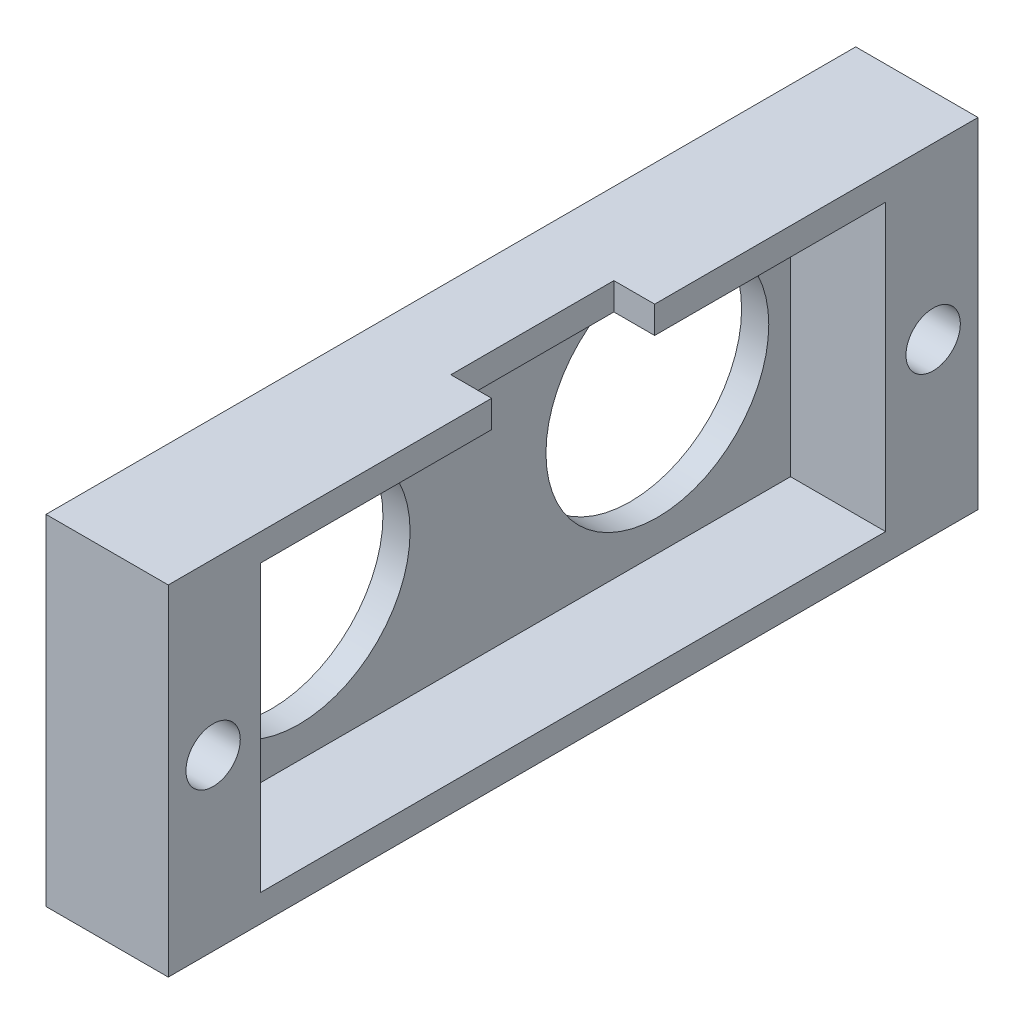
SolidWorks part; units mm, degrees
ref_plane "Front" through (0, 0, 0) normal (0, 0, 1) x (1, 0, 0)
ref_plane "Top" through (0, 0, 0) normal (0, 1, 0) x (1, 0, 0)
ref_plane "Right" through (0, 0, 0) normal (1, 0, 0) x (0, 0, -1)
sketch "Sketch1" plane through (0, 0, 0) normal (1, 0, 0) x (0, 0, -1)
  line L0 (-25, 0) -> (-21.4, 0) construction
  line L1 (-25, 12.5) -> (25, 12.5)
  line L2 (-25, 12.5) -> (-25, -12.5) construction
  line L3 (-25, -12.5) -> (25, -12.5)
  line L4 (25, 12.5) -> (25, -12.5) construction
  line L5 (0, 12.5) -> (0, -12.5) construction
  line L6 (-5, 0) -> (5, 0) construction
  line L7 (21.4, 0) -> (25, 0) construction
  line L8 (-21.4, 0) -> (-5, 0) construction
  line L9 (5, 0) -> (21.4, 0) construction
  line L11 (-23, 10.5) -> (23, 10.5) construction
  line L12 (-23, 10.5) -> (-23, -10.5) construction
  line L13 (-23, -10.5) -> (23, -10.5) construction
  line L14 (23, 10.5) -> (23, -10.5) construction
  line L18 (-25, 12.5) -> (-29.8, 12.5)
  line L19 (-29.8, 12.5) -> (-29.8, -12.5)
  line L20 (-29.8, -12.5) -> (-25, -12.5)
  line L21 (25, -12.5) -> (29.8, -12.5)
  line L22 (29.8, -12.5) -> (29.8, 12.5)
  line L23 (29.8, 12.5) -> (25, 12.5)
  circle A0 centre (13.2, 0) radius 8.2
  circle A1 centre (-13.2, 0) radius 8.2
  circle A2 centre (-26.5, 0) radius 2
  circle A3 centre (26.5, 0) radius 2
  dimension "D2" = 16.4
  dimension "D8" = 4
  dimension "D1" = 26.4
  dimension "D3" = 50
  dimension "D4" = 25
  dimension "D5" = 46
  dimension "D6" = 21
  dimension "D7" = 53
  dimension "D9" = 59.6
extrude "Boss-Extrude1" add sketch "Sketch1" along normal blind 2
sketch "Sketch3" plane through (2, 0, 0) normal (1, 0, 0) x (0, 0, -1)
  line L0 (0, -12.5) -> (0, 12.5) construction
  line L1 (-23, 10.5) -> (23, 10.5)
  line L2 (-23, 10.5) -> (-23, -10.5)
  line L3 (-23, -10.5) -> (23, -10.5)
  line L4 (23, 10.5) -> (23, -10.5)
  line L5 (-29.8, -12.5) -> (29.8, -12.5) construction
  line L6 (-29.8, 12.5) -> (29.8, 12.5) construction
  line L7 (23, 10.5) -> (-23, -10.5) construction
  line L12 (29.8, -12.5) -> (29.8, 12.5)
  line L13 (29.8, -12.5) -> (29.8, 12.5)
  line L14 (-29.8, 12.5) -> (-29.8, -12.5)
  line L15 (-29.8, 12.5) -> (-29.8, -12.5)
  line L17 (29.8, 12.5) -> (-29.8, 12.5)
  line L19 (-29.8, -12.5) -> (29.8, -12.5)
  line L23 (29.8, 12.5) -> (-29.8, 12.5)
  line L25 (-29.8, -12.5) -> (29.8, -12.5)
  circle A0 centre (-26.5, 0) radius 2 construction
  circle A1 centre (26.5, 0) radius 2 construction
  circle A2 centre (-26.5, 0) radius 2
  circle A3 centre (26.5, 0) radius 2
  dimension "D2" = 46
  dimension "D3" = 21
  dimension "D1" = 0
extrude "Boss-Extrude3" add sketch "Sketch3" along normal blind 7
sketch "Sketch5" plane through (0, 12.5, 0) normal (0, 1, 0) x (1, 0, 0)
  line L0 (9, 6) -> (6, 6)
  line L1 (9, 29.8) -> (9, -29.8) construction
  line L2 (6, 6) -> (6, -6)
  line L3 (6, -6) -> (9, -6)
  line L4 (6, 0) -> (9, 0) construction
  dimension "D1" = 3
  dimension "D2" = 12
extrude "Cut-Extrude1" cut sketch "Sketch5" against normal blind 3 and the other way through all
